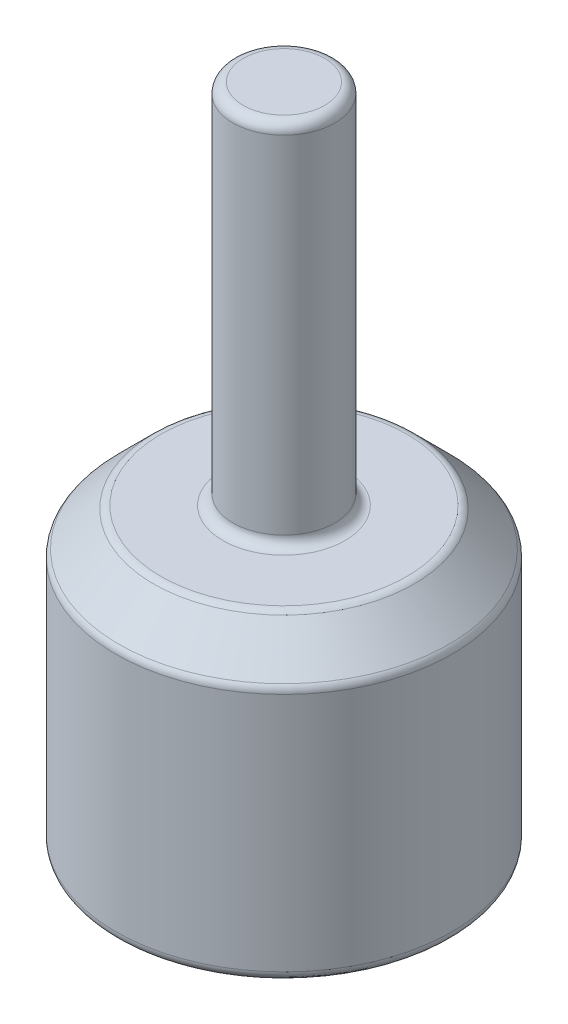
SolidWorks part; units mm, degrees
ref_plane "Front Plane" through (0, 0, 0) normal (0, 0, 1) x (1, 0, 0)
ref_plane "Top Plane" through (0, 0, 0) normal (0, 1, 0) x (1, 0, 0)
ref_plane "Right Plane" through (0, 0, 0) normal (1, 0, 0) x (0, 0, -1)
sketch "Sketch1" plane through (0, 0, 0) normal (0, 0, 1) x (1, 0, 0)
  line L0 (0, 0) -> (2, 0)
  line L1 (2.5, -0.5) -> (2.5, -17.5)
  line L2 (3, -18) -> (6.0429, -18)
  line L3 (6.3964, -18.1464) -> (8.1036, -19.8536)
  line L4 (8.25, -20.2071) -> (8.25, -32)
  line L5 (7.75, -32.5) -> (7.25, -32.5)
  line L6 (0, 0) -> (0, -35)
  line L7 (0, -35) -> (-7.5772, -35) construction
  arc A0 (0, -35) -> (7.25, -32.5) centre (0, -23.2375) ccw
  arc A1 (2.5, -0.5) -> (2, 0) centre (2, -0.5) ccw
  arc A2 (3, -18) -> (2.5, -17.5) centre (3, -17.5) cw
  arc A3 (8.25, -20.2071) -> (8.1036, -19.8536) centre (7.75, -20.2071) ccw
  arc A4 (6.3964, -18.1464) -> (6.0429, -18) centre (6.0429, -18.5) ccw
  arc A5 (8.25, -32) -> (7.75, -32.5) centre (7.75, -32) cw
  point P13 (2.5, 0)
  point P16 (2.5, -18)
  point P19 (8.25, -20)
  point P22 (6.25, -18)
  point P25 (8.25, -32.5)
  dimension "D9" = 0.5
  dimension "D1" = 8.25
  dimension "D2" = 14.5
  dimension "D3" = 2.5
  dimension "D4" = 1
  dimension "D5" = 18
  dimension "D6" = 2
  dimension "D7" = 2
  dimension "D8" = 2.5
revolve "Revolve1" add sketch "Sketch1" angle 360 about L6
